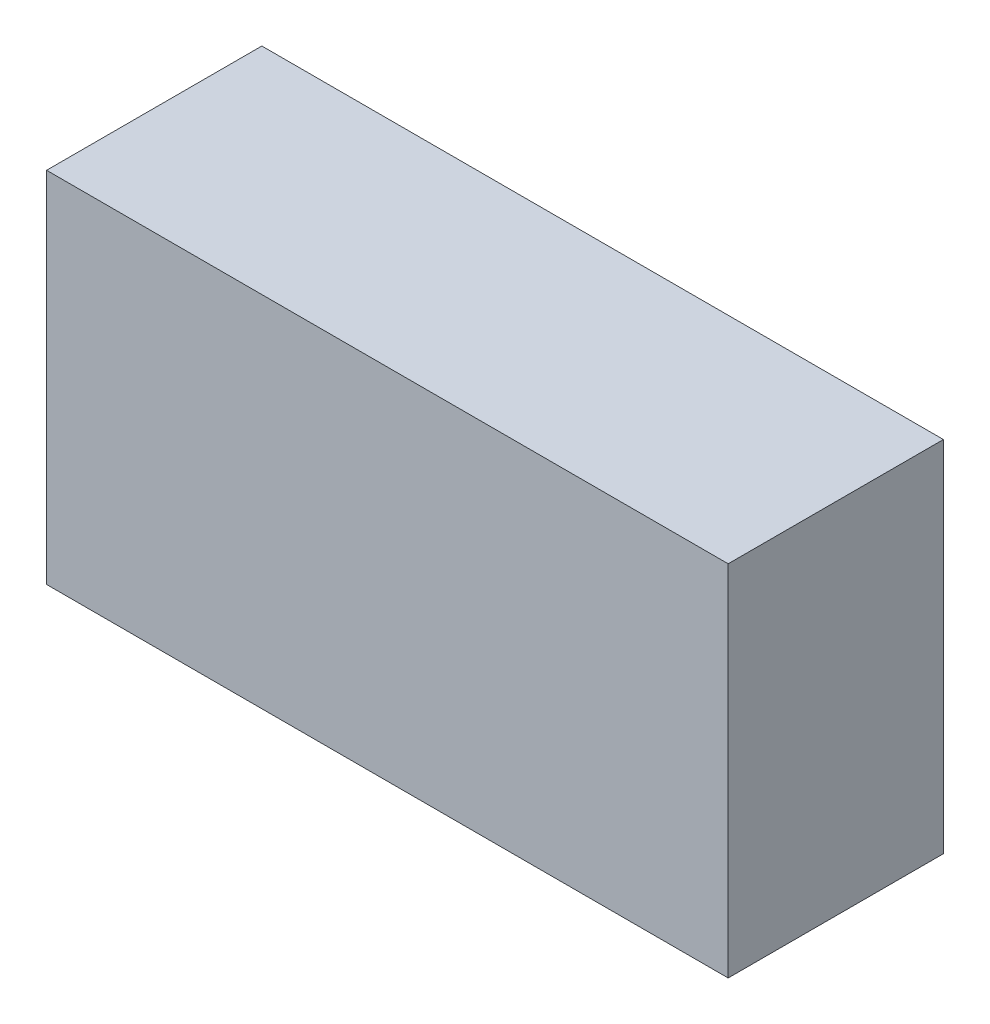
SolidWorks part; units mm, degrees
ref_plane "Front Plane" through (0, 0, 0) normal (0, 0, 1) x (1, 0, 0)
ref_plane "Top Plane" through (0, 0, 0) normal (0, 1, 0) x (1, 0, 0)
ref_plane "Right Plane" through (0, 0, 0) normal (1, 0, 0) x (0, 0, -1)
sketch "Sketch1" plane through (0, 0, 0) normal (0, 1, 0) x (1, 0, 0)
  line L1 (-190, -60) -> (190, -60)
  line L2 (-190, -60) -> (-190, 60)
  line L3 (-190, 60) -> (190, 60)
  line L4 (190, -60) -> (190, 60)
  line L5 (-190, -60) -> (190, 60) construction
  line L6 (-190, 60) -> (190, -60) construction
  point P0 (0, 0)
  dimension "D1" = 120
  dimension "D2" = 380
extrude "Boss-Extrude1" add sketch "Sketch1" along normal blind 200
